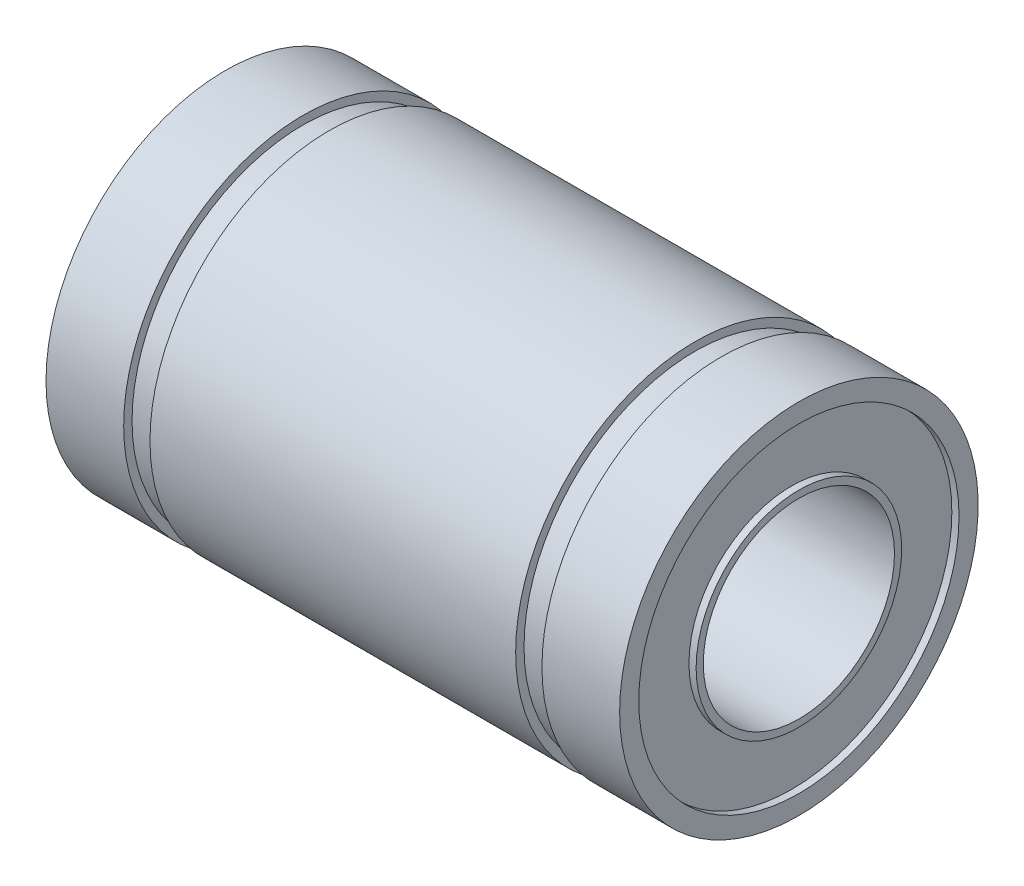
SolidWorks part; units mm, degrees
material "Plain Carbon Steel"
ref_plane "Front Plane" through (0, 0, 0) normal (0, 0, 1) x (1, 0, 0)
ref_plane "Top Plane" through (0, 0, 0) normal (0, 1, 0) x (1, 0, 0)
ref_plane "Right Plane" through (0, 0, 0) normal (1, 0, 0) x (0, 0, -1)
sketch "Sketch1" plane through (0, 0, 0) normal (0, 0, 1) x (1, 0, 0)
  line L0 (-12, 0) -> (12, 0) construction
  line L1 (-12, 4) -> (12, 4)
  line L2 (-12, 4) -> (-12, 4.3)
  line L3 (-12, 7.5) -> (-8.75, 7.5)
  line L4 (12, 4) -> (12, 4.3)
  line L5 (8.75, 7.5) -> (12, 7.5)
  line L6 (-12, 6.7) -> (-11.7, 6.7)
  line L7 (0, 0) -> (0, 1.809) construction
  line L8 (-12, 4.3) -> (-11.7, 4.3)
  line L9 (-11.7, 6.7) -> (-11.7, 4.3)
  line L10 (-12, 6.7) -> (-12, 7.5)
  line L11 (-8.75, 7.5) -> (-8.75, 7.15)
  line L12 (-8.75, 7.15) -> (-7.65, 7.15)
  line L13 (-7.65, 7.5) -> (-7.65, 7.15)
  line L14 (-7.65, 7.5) -> (7.65, 7.5)
  line L15 (8.75, 7.5) -> (8.75, 7.15)
  line L16 (8.75, 7.15) -> (7.65, 7.15)
  line L17 (7.65, 7.5) -> (7.65, 7.15)
  line L18 (11.7, 6.7) -> (11.7, 4.3)
  line L19 (12, 4.3) -> (11.7, 4.3)
  line L20 (12, 6.7) -> (11.7, 6.7)
  line L21 (12, 6.7) -> (12, 7.5)
  point P21 (12, 7.5)
  point P24 (-12, 7.5)
  dimension "D1" = 8
  dimension "D2" = 15
  dimension "D3" = 24
  dimension "D4" = 0.3
  dimension "D5" = 0.3
  dimension "D6" = 0.8
  dimension "D7" = 17.5
  dimension "D8" = 1.1
  dimension "D9" = 14.3
revolve "Revolve1" add sketch "Sketch1" angle 360 about L0
